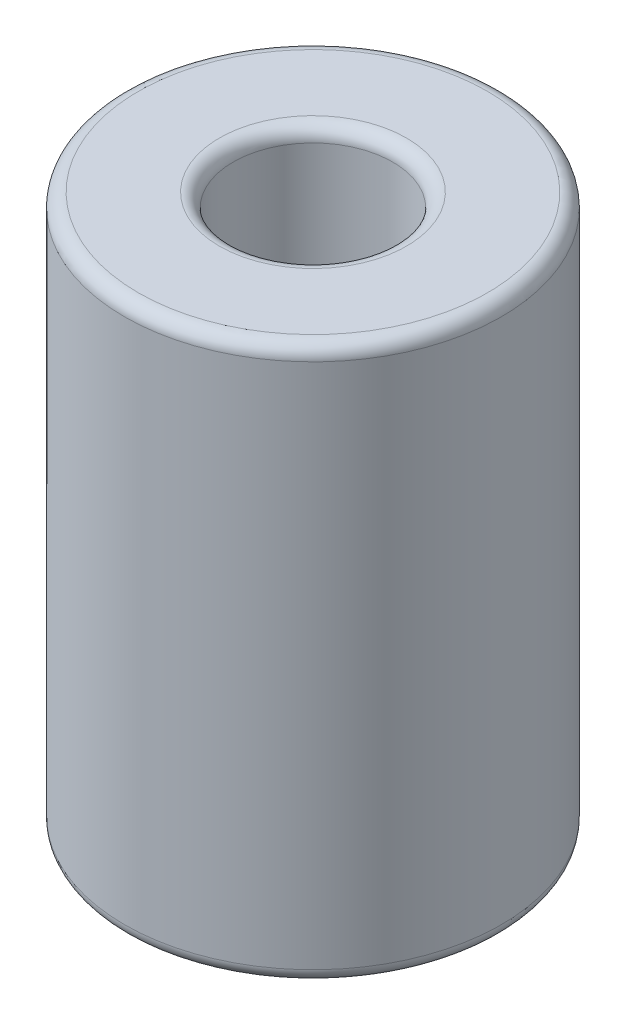
SolidWorks part; units mm, degrees
ref_plane "Front Plane" through (0, 0, 0) normal (0, 0, 1) x (1, 0, 0)
ref_plane "Top Plane" through (0, 0, 0) normal (0, 1, 0) x (1, 0, 0)
ref_plane "Right Plane" through (0, 0, 0) normal (1, 0, 0) x (0, 0, -1)
sketch "Sketch1" plane through (0, 0, 0) normal (0, 1, 0) x (1, 0, 0)
  circle A0 centre (0, 0) radius 2.286
  circle A1 centre (0, 0) radius 5.3975
  dimension "D1" = 4.572
  dimension "D2" = 10.795
extrude "Boss-Extrude1" add sketch "Sketch1" along normal blind 15.875
fillet "Fillet1" radius 0.3969 4 edges at (0, 0, 2.286) (0, 0, 5.3975) (0, 15.875, 2.286) (0, 15.875, 5.3975)
